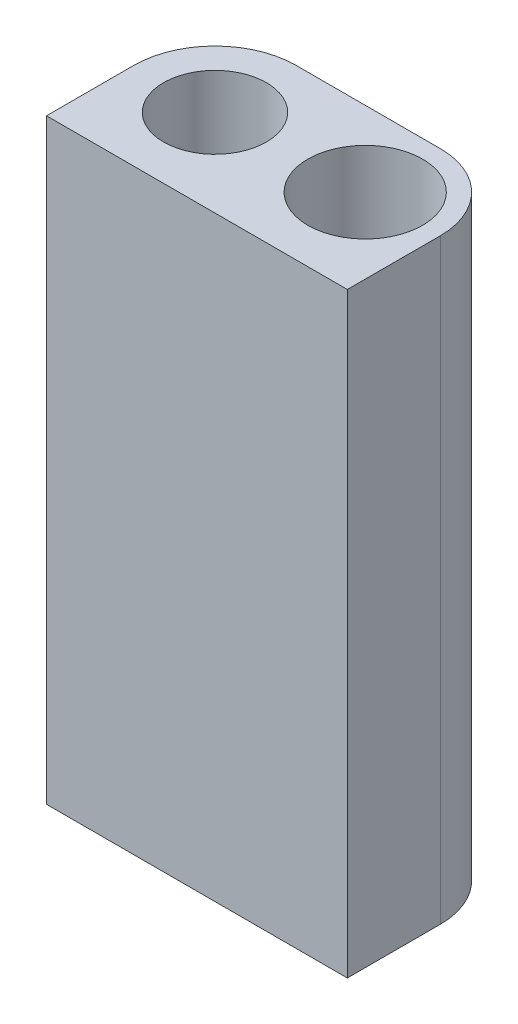
SolidWorks part; units mm, degrees
ref_plane "Front Plane" through (0, 0, 0) normal (0, 0, 1) x (1, 0, 0)
ref_plane "Top Plane" through (0, 0, 0) normal (0, 1, 0) x (1, 0, 0)
ref_plane "Right Plane" through (0, 0, 0) normal (1, 0, 0) x (0, 0, -1)
sketch "Sketch1" plane through (0, 0, 0) normal (0, 1, 0) x (1, 0, 0)
  line L0 (0, -55) -> (0, 55) construction
  line L1 (-5.45, 0) -> (3.45, 0)
  line L2 (-5.45, 0) -> (-5.45, -5.85)
  line L3 (-5.45, -5.85) -> (5.45, -5.85)
  line L5 (3.45, 0) -> (5.85, 0) construction
  line L6 (0, 5.45) -> (9.6792, 5.45)
  line L7 (14.7292, 0.4) -> (14.7292, -5.85)
  line L8 (14.7292, -5.85) -> (5.45, -5.85)
  line L10 (0, -3.45) -> (9.6792, -3.45) construction
  line L11 (0, -3.45) -> (0, -5.85)
  circle A0 centre (0, 0) radius 3.45
  circle A2 centre (9.6792, 0.4) radius 3.85
  arc A3 (14.7292, 0.4) -> (9.6792, 5.45) centre (9.6792, 0.4) ccw
  arc A4 (0, 5.45) -> (-5.45, 0) centre (0, 0) ccw
  point P8 (0, -5.85)
  dimension "D1" = 6.9
  dimension "D2" = 2.4
  dimension "D3" = 7.7
  dimension "D4" = 10.1
  dimension "D5" = 2.4
extrude "Boss-Extrude2" add sketch "Sketch1" along normal blind 40 contours L6 A4 L1 A0 L11 L3 L8 L7 A3 A2 | A0 L1 L2 L3 L11
